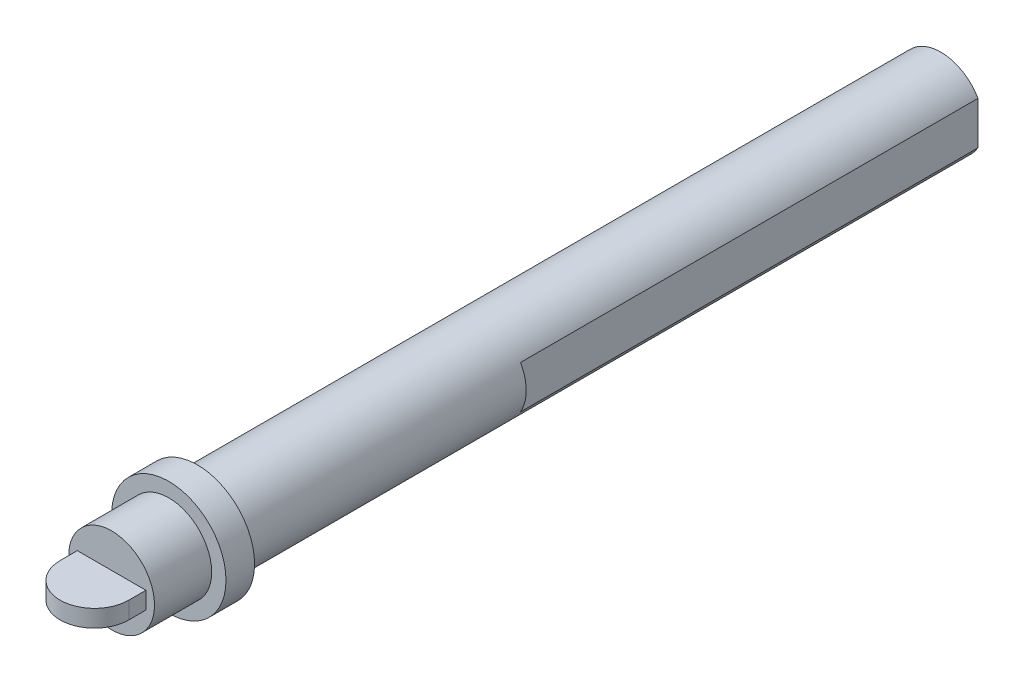
SolidWorks part; units mm, degrees
ref_plane "Front Plane" through (0, 0, 0) normal (0, 0, 1) x (1, 0, 0)
ref_plane "Top Plane" through (0, 0, 0) normal (0, 1, 0) x (1, 0, 0)
ref_plane "Right Plane" through (0, 0, 0) normal (1, 0, 0) x (0, 0, -1)
sketch "Sketch1" plane through (0, 0, 0) normal (0, 0, 1) x (1, 0, 0)
  circle A0 centre (0, 0) radius 7.5
  dimension "D1" = 15
extrude "Boss-Extrude1" add sketch "Sketch1" against normal blind 130
sketch "Sketch2" plane through (0, 0, 0) normal (0, 0, 1) x (1, 0, 0)
  circle A0 centre (0, 0) radius 10
  dimension "D1" = 20
extrude "Boss-Extrude2" add sketch "Sketch2" along normal blind 5
sketch "Sketch3" plane through (0, 0, 5) normal (0, 0, 1) x (1, 0, 0)
  circle A0 centre (0, 0) radius 7.5 construction
  circle A1 centre (0, 0) radius 7.5
extrude "Boss-Extrude3" add sketch "Sketch3" along normal blind 10
sketch "Sketch4" plane through (0, 0, -130) normal (0, 0, -1) x (-1, 0, 0)
  line L0 (-6.5, 3.7417) -> (-6.5, -3.7417)
  line L2 (6.5, 3.7417) -> (6.5, -3.7417)
  circle A0 centre (0, 0) radius 7.5 construction
  arc A2 (-6.5, 3.7417) -> (-6.5, -3.7417) centre (0, 0) ccw
  arc A3 (6.5, -3.7417) -> (6.5, 3.7417) centre (0, 0) ccw
  dimension "D1" = 6.5
extrude "Cut-Extrude1" cut sketch "Sketch4" against normal blind 80
sketch "Sketch6" plane through (0, 0, 0) normal (0, 1, 0) x (1, 0, 0)
  line L0 (0, -18) -> (0, -9.3176) construction
  line L1 (-6, -18) -> (-6, -15)
  line L2 (6, -18) -> (6, -15)
  line L3 (-6, -15) -> (6, -15)
  line L4 (-7.5, -15) -> (7.5, -15) construction
  arc A0 (-6, -18) -> (6, -18) centre (0, -18) ccw
  point P3 (0, -13.6588)
  dimension "D3" = 6
  dimension "D1" = 0
  dimension "D2" = 3
  dimension "D4" = 3
  dimension "D5" = 12
  dimension "D6" = 6
extrude "Boss-Extrude4" add sketch "Sketch6" along normal mid plane 3
